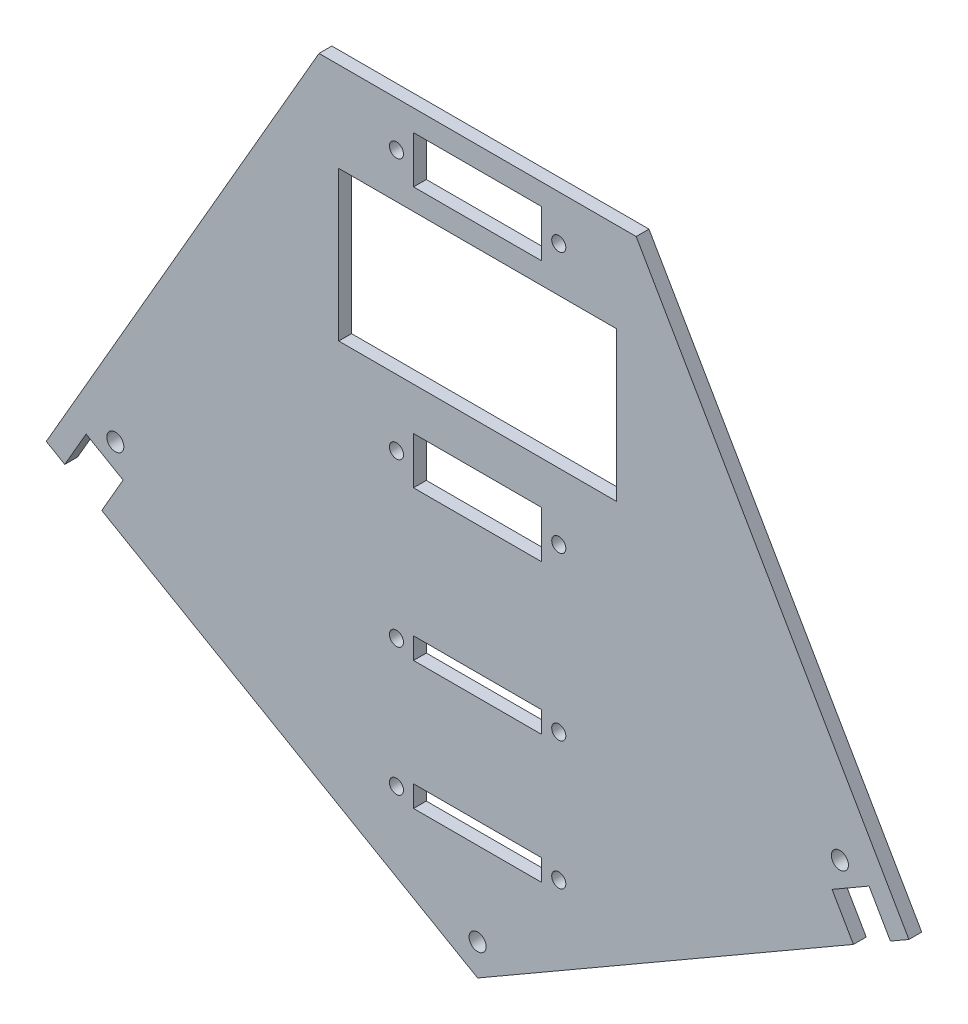
SolidWorks part; units mm, degrees
ref_plane "Plan de face" through (0, 0, 0) normal (0, 0, 1) x (1, 0, 0)
ref_plane "Plan de dessus" through (0, 0, 0) normal (0, 1, 0) x (1, 0, 0)
ref_plane "Plan de droite" through (0, 0, 0) normal (1, 0, 0) x (0, 0, -1)
sketch "Esquisse1" plane through (0, 0, 0) normal (0, 0, 1) x (1, 0, 0)
  line L0 (-32.5, 112.872) -> (32.5, 112.872)
  line L1 (32.5, 112.872) -> (114, -28.2902) construction
  line L2 (-83.1038, 69.2236) -> (-98.1666, 43.134) construction
  line L3 (81.5, -84.5818) -> (-81.5, -84.5818) construction
  line L4 (76.8826, 79.9991) -> (97.4316, 44.4072) construction
  line L5 (-114, -28.2902) -> (-32.5, 112.872) construction
  line L6 (-15, 61.872) -> (15, 61.872)
  line L7 (0, 84.8951) -> (0, 0) construction
  line L8 (15, 61.872) -> (15, 56.872)
  line L9 (108.528, -62.6587) -> (-0.0727, 0.042) construction
  line L10 (0, 0) -> (-107.4388, -62.0298) construction
  line L11 (15, 56.872) -> (-15, 56.872)
  line L12 (-15, 56.872) -> (-15, 61.872)
  line L13 (26.3257, 59.372) -> (-26.3257, 59.372) construction
  line L14 (15, 31.872) -> (15, 26.872)
  line L15 (15, 26.872) -> (-15, 26.872)
  line L16 (-15, 31.872) -> (15, 31.872)
  line L17 (-15, 102.872) -> (15, 102.872)
  line L18 (15, 102.872) -> (15, 91.872)
  line L19 (15, 91.872) -> (-15, 91.872)
  line L20 (-15, 91.872) -> (-15, 102.872)
  line L21 (-15, 26.872) -> (-15, 31.872)
  line L22 (-32.5, 112.872) -> (-32.5, 147.872)
  line L23 (-24.2975, 29.372) -> (23.7598, 29.372) construction
  line L24 (-139.9808, -43.2902) -> (-32.5, 142.872) construction
  line L25 (32.5, 142.872) -> (139.9808, -43.2902) construction
  line L26 (-32.5, 147.872) -> (32.5, 147.872)
  line L27 (32.5, 147.872) -> (32.5, 112.872)
  line L29 (-81.5, -84.5818) -> (-44.8099, -84.5818) construction
  line L32 (44.8099, -84.5818) -> (81.5, -84.5818) construction
  line L35 (-207.1218, -119.5818) -> (207.1218, -119.5818) construction
  line L36 (37.1188, 168.872) -> (100.9628, 58.2909)
  line L37 (-96.6327, 55.7909) -> (-100.9628, 58.2909)
  line L38 (-37.1188, 168.872) -> (37.1188, 168.872)
  line L39 (-37.1188, 168.872) -> (-100.9628, 58.2909)
  line L40 (100.9628, 58.2909) -> (96.6327, 55.7909)
  line L41 (96.6327, 55.7909) -> (91.6327, 64.4512)
  line L42 (87.9724, 50.7909) -> (82.9724, 59.4512)
  line L44 (-49.8692, 127.872) -> (56.9381, 127.872) construction
  line L45 (15, 102.872) -> (-15, 102.872)
  line L46 (-15, 91.872) -> (15, 91.872)
  line L47 (26.3257, 158.372) -> (-26.3257, 158.372) construction
  line L48 (0, 170.3911) -> (0, 255.2862) construction
  line L49 (-15, 163.872) -> (15, 163.872)
  line L50 (15, 152.872) -> (-15, 152.872)
  line L51 (-15, 163.872) -> (-15, 152.872)
  line L52 (15, 163.872) -> (-15, 163.872)
  line L53 (15, 152.872) -> (15, 163.872)
  line L54 (-15, 152.872) -> (15, 152.872)
  line L55 (91.6327, 64.4512) -> (82.9724, 59.4512)
  line L56 (87.9724, 50.7909) -> (0, 0)
  line L57 (26.3257, 97.372) -> (-26.3257, 97.372) construction
  line L58 (-96.6327, 55.7909) -> (-91.6327, 64.4512)
  line L59 (-87.9724, 50.7909) -> (-82.9724, 59.4512)
  line L60 (62.2558, -82.9138) -> (101.7182, -14.5628) construction
  line L62 (-91.6327, 64.4512) -> (-82.9724, 59.4512)
  line L64 (-139.9808, -43.2902) -> (-32.5, 142.872) construction
  line L67 (32.5, 142.872) -> (139.9808, -43.2902) construction
  line L70 (-107.4808, -99.5818) -> (107.4808, -99.5818) construction
  line L72 (-87.9724, 50.7909) -> (0, 0)
  circle A0 centre (-84.8026, 66.2813) radius 2
  circle A1 centre (84.8026, 66.2813) radius 2
  circle A2 centre (-19, 97.372) radius 1.65
  circle A3 centre (19, 97.372) radius 1.65
  circle A4 centre (19, 158.372) radius 1.65
  circle A5 centre (-19, 158.372) radius 1.65
  circle A6 centre (-19, 59.372) radius 1.65
  circle A7 centre (0, 7.3429) radius 2
  circle A8 centre (19, 59.372) radius 1.65
  circle A9 centre (19, 29.372) radius 1.65
  circle A10 centre (-19, 29.372) radius 1.65
  point P12 (-87.3026, 61.9512)
  point P15 (87.3026, 61.9512)
  point P93 (-15, 29.372)
  dimension "D18" = 30
  dimension "D33" = 38
  dimension "D19" = 5
  dimension "D6" = 15
  dimension "D7" = 15
  dimension "D2" = 120
  dimension "D4" = 35
  dimension "D5" = 197.4538
  dimension "D8" = 10
  dimension "D9" = 4
  dimension "D10" = 10
  dimension "D11" = 4
  dimension "D12" = 5
  dimension "D13" = 65
  dimension "D14" = 2
  dimension "D15" = 30
  dimension "D16" = 10
  dimension "D17" = 2
  dimension "D20" = 5
  dimension "D21" = 5
  dimension "D22" = 5
  dimension "D23" = 10
  dimension "D24" = 10
  dimension "D25" = 30
  dimension "D26" = 11
extrude "Boss.-Extru.1" add sketch "Esquisse1" along normal blind 3
sketch "Esquisse2" plane through (0, 0, 0) normal (0, 0, -1) x (-1, 0, 0)
  line L0 (-87.9724, 50.7909) -> (0, 0) construction
  line L1 (-45.4276, 26.2277) -> (-79.3214, 45.7962)
  arc A0 (-79.3214, 45.7962) -> (-45.4276, 26.2277) centre (-62.3961, 35.9745) cw
